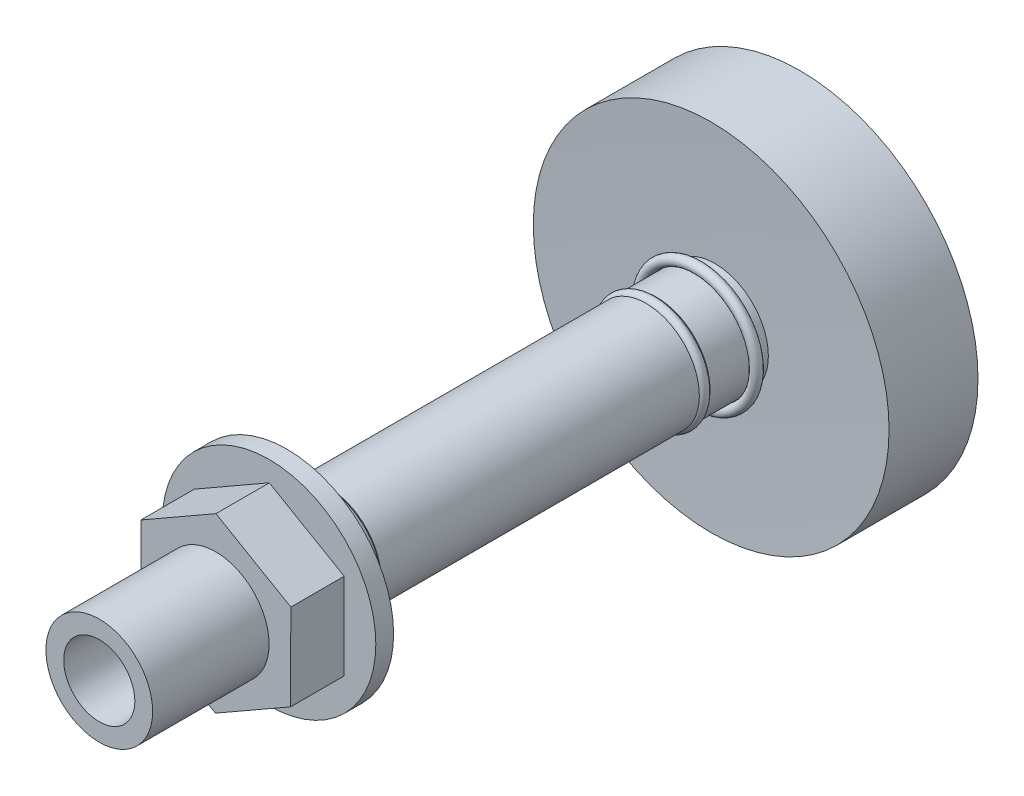
SolidWorks part; units mm, degrees
ref_plane "Front Plane" through (0, 0, 0) normal (0, 0, 1) x (1, 0, 0)
ref_plane "Top Plane" through (0, 0, 0) normal (0, 1, 0) x (1, 0, 0)
ref_plane "Right Plane" through (0, 0, 0) normal (1, 0, 0) x (0, 0, -1)
sketch "Sketch2" plane through (0, 0, 0) normal (1, 0, 0) x (0, 0, -1)
  line L0 (-82.8882, 0) -> (83.7577, 0) construction
  line L1 (-68.6871, 10) -> (-54.1961, 10)
  line L2 (-54.1961, 10) -> (-54.1961, 5.2)
  line L3 (-54.1961, 5.2) -> (54.6949, 5.2)
  line L4 (54.6949, 5.2) -> (54.6949, 10)
  line L5 (54.6949, 10) -> (94.6949, 10)
  line L6 (94.6949, 10) -> (94.6949, 50)
  line L7 (94.6949, 50) -> (69.6949, 50)
  line L9 (94.6949, 15) -> (-49.2314, 15)
  line L11 (-49.569, 30) -> (-69.569, 30)
  line L12 (-69.569, 30) -> (-69.569, 15)
  line L13 (-69.569, 15) -> (-102.3061, 15)
  line L14 (-102.3061, 15) -> (-102.3061, 10)
  line L15 (-102.3061, 10) -> (-68.6871, 10)
  line L16 (94.6949, 15) -> (70.7686, 15)
  arc A0 (-49.2314, 15) -> (-49.569, 30) centre (-1049.1189, 0) ccw
  arc A1 (70.7686, 15) -> (69.6949, 50) centre (-989.1252, 0) ccw
  dimension "D14" = 2000
  dimension "D12" = 2120
  dimension "D2" = 5.2
  dimension "D3" = 10
  dimension "D4" = 10
  dimension "D5" = 5
  dimension "D6" = 30
  dimension "D7" = 50
  dimension "D8" = 40
  dimension "D9" = 15
  dimension "D10" = 20
  dimension "D11" = 25
  dimension "D13" = 120
revolve "Revolve1" add sketch "Sketch2" angle 360 about L0
sketch "Sketch3" plane through (0, 0, 0) normal (0, 1, 0) x (1, 0, 0)
  line L1 (9.7804, 61.4892) -> (4.7804, 61.4892)
  line L2 (9.7804, 61.4892) -> (9.7804, 49.4892)
  line L3 (9.7804, 49.4892) -> (4.7804, 49.4892)
  line L4 (4.7804, 61.4892) -> (4.7804, 49.4892)
  line L5 (0, 27.0222) -> (0, -36.1697) construction
  line L6 (9.9377, -54.2645) -> (4.9377, -54.2645)
  line L7 (9.9377, -54.2645) -> (9.9377, -66.2645)
  line L8 (9.9377, -66.2645) -> (4.9377, -66.2645)
  line L9 (4.9377, -54.2645) -> (4.9377, -66.2645)
  dimension "D1" = 5
  dimension "D2" = 12
  dimension "D3" = 5
  dimension "D4" = 12
revolve "Revolve2" add sketch "Sketch3" angle 360 about L5
sketch "Sketch4" plane through (0, 0, 0) normal (0, 1, 0) x (1, 0, 0)
  line L1 (5.1844, 46.1353) -> (7.1844, 46.1342)
  line L2 (5.1844, 46.1353) -> (5.1844, 43.1342)
  line L3 (5.1844, 43.1342) -> (7.1844, 43.1342)
  line L4 (7.1844, 46.1342) -> (7.1844, 43.1342)
  line L5 (5.1671, -46.0486) -> (7.1671, -46.0486)
  line L6 (5.1671, -46.0486) -> (5.1671, -49.0486)
  line L7 (5.1671, -49.0486) -> (7.1671, -49.0486)
  line L8 (7.1671, -46.0486) -> (7.1671, -49.0486)
  line L14 (15.0008, 54.3777) -> (13.0008, 54.3777)
  line L15 (15.0008, 54.3777) -> (15.0008, 51.3777)
  line L16 (15.0008, 51.3777) -> (13.0008, 51.3777)
  line L17 (13.0008, 54.3777) -> (13.0008, 51.3777)
  line L23 (0, 31.3382) -> (0, -16.0514) construction
  line L24 (15.0082, -38.0516) -> (13.0082, -38.0516)
  line L25 (15.0082, -38.0516) -> (15.0082, -41.0516)
  line L26 (15.0082, -41.0516) -> (13.0082, -41.0516)
  line L27 (13.0082, -38.0516) -> (13.0082, -41.0516)
  line L28 (14.9998, -55.3051) -> (17.9998, -55.3051)
  line L34 (14.9998, -55.3051) -> (14.9998, -57.3051)
  line L35 (14.9998, -57.3051) -> (17.9998, -57.3051)
  line L36 (17.9998, -55.3051) -> (17.9998, -57.3051)
  line L38 (15.0065, 65.3648) -> (18.0065, 65.3648)
  line L39 (15.0065, 65.3648) -> (15.0065, 67.3648)
  line L40 (15.0065, 67.3648) -> (18.0065, 67.3648)
  line L41 (18.0065, 65.3648) -> (18.0065, 67.3648)
  dimension "D1" = 3
  dimension "D2" = 2
  dimension "D3" = 2
  dimension "D4" = 3
  dimension "D5" = 2
  dimension "D6" = 3
  dimension "D7" = 2
  dimension "D8" = 3
  dimension "D9" = 2
  dimension "D10" = 3
  dimension "D11" = 2
  dimension "D12" = 3
revolve "Cut-Revolve1" cut sketch "Sketch4" angle 360 about L23
sketch "Sketch5" plane through (0, 0, 0) normal (0, 1, 0) x (1, 0, 0)
  line L0 (0, 40.6102) -> (0, 26.4444) construction
  circle A0 centre (16.501, 65.8942) radius 1.4
  circle A1 centre (14.4375, 52.8864) radius 1.4
  circle A2 centre (5.7322, 44.6572) radius 1.4
  circle A3 centre (14.4375, -39.5674) radius 1.4
  circle A4 centre (5.7322, -47.5621) radius 1.4
  circle A5 centre (16.501, -55.8575) radius 1.4
  dimension "D1" = 2.8
  dimension "D2" = 2.8
  dimension "D3" = 2.8
  dimension "D4" = 2.8
  dimension "D5" = 2.8
  dimension "D6" = 2.8
revolve "Revolve3" add sketch "Sketch5" angle 360 about L0
sketch "Sketch6" plane through (0, 0, 69.569) normal (0, 0, 1) x (1, 0, 0)
  line L0 (0, 0) -> (21.0689, -0.0664) construction
  line L1 (21.0306, -12.2305) -> (21.1072, 12.0977)
  line L2 (21.1072, 12.0977) -> (0.0767, 24.3283)
  line L3 (0.0767, 24.3283) -> (-21.0306, 12.2305)
  line L4 (-21.0306, 12.2305) -> (-21.1072, -12.0977)
  line L5 (-21.1072, -12.0977) -> (-0.0767, -24.3283)
  line L6 (-0.0767, -24.3283) -> (21.0306, -12.2305)
  line L7 (0, 0) -> (21.1072, 12.0977) construction
  circle A0 centre (0, 0) radius 21.069 construction
  circle A1 centre (0, 0) radius 30
extrude "Cut-Extrude1" cut sketch "Sketch6" against normal blind 15
equation "\"mountAngle\" = 30deg"
equation "\"ThrusterDim\"= 140mm"
equation "\"hatchHoleDiameter\"= 600mm"
equation "\"hullThickness\"= 120mm"
equation "\"gasketHullInterconnectWidth\"= 100mm"
equation "\"collarThickness\"= 15"
equation "\"hatchTunnelLength\"=200"
equation "\"oRingDiameter\"=2"
equation "\"boltPatternRadiusInterconnect\"=500"
equation "\"interconnectBoltDiameter\"=30"
equation "\"hatchShaftDiameter\"=20"
equation "\"hatchMinima\"=50"
equation "\"hullDiameter\"=2000"
equation "\"hatchMaxima\"=180"
equation "\"bushingFlatHatch\"=15"
equation "\"hingePivotDiameter\"=20"
equation "\"handleWidth\"=250"
equation "\"handleHeight\"=160"
equation "\"handleThickness\"=25"
equation "\"FrameLength\"= 4300"
equation "\"FrameMidLength\"= 3000"
equation "\"TubeOD\"= 100"
equation "\"FrameBackFlat\"= 800"
equation "\"TubeWall\"=15"
equation "\"TopMemberAngle\"=120"
equation "\"FrameHight\"= 2500"
equation "\"D12@Sketch2\"=\"hullThickness\" + \"hullDiameter\""
equation "\"D13@Sketch2\"=\"hullThickness\""
